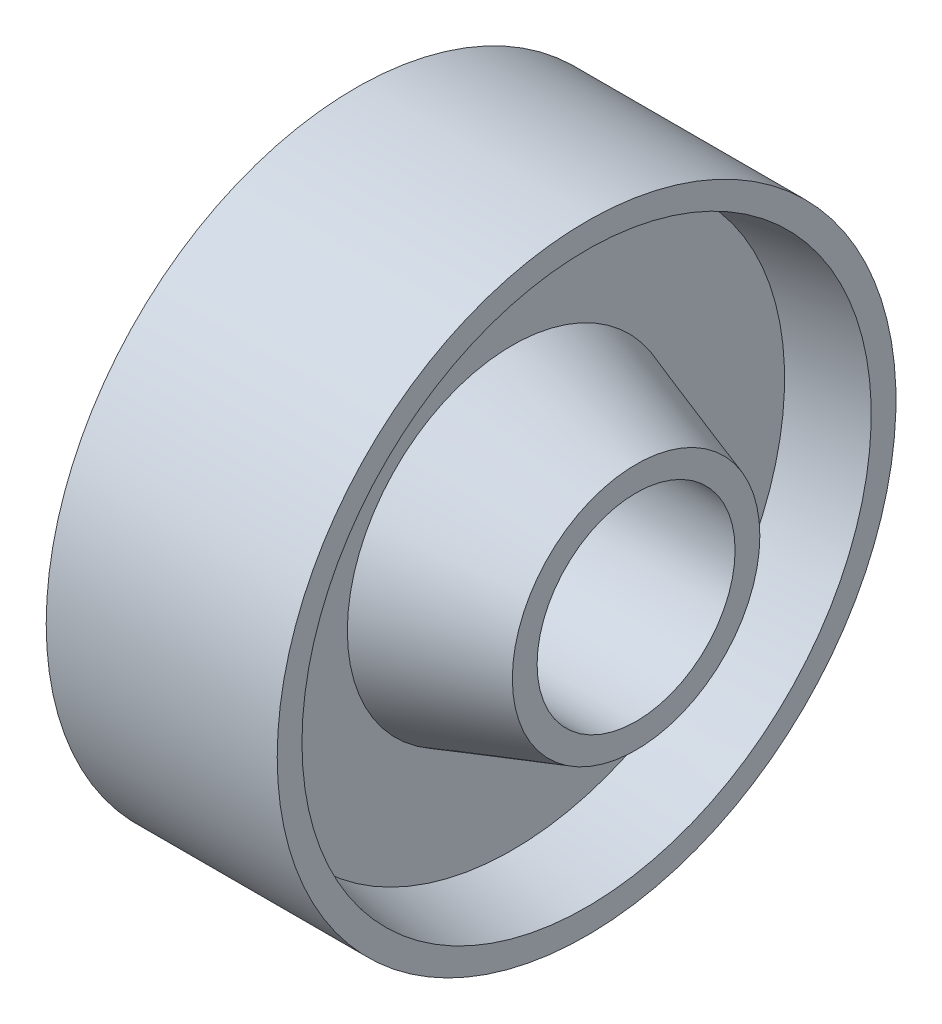
SolidWorks part; units mm, degrees
ref_plane "Front Plane" through (0, 0, 0) normal (0, 0, 1) x (1, 0, 0)
ref_plane "Top Plane" through (0, 0, 0) normal (0, 1, 0) x (1, 0, 0)
ref_plane "Right Plane" through (0, 0, 0) normal (1, 0, 0) x (0, 0, -1)
sketch "Sketch1" plane through (0, 0, 0) normal (0, 0, 1) x (1, 0, 0)
  line L0 (0, 0) -> (0, -12) construction
  line L1 (-20, -12) -> (20, -12)
  line L2 (0, 0) -> (50000, 0) construction
  line L3 (-20, -15) -> (20, -15)
  line L5 (-5, -20) -> (5, -20)
  line L7 (-5, -33) -> (5, -33)
  line L9 (-14, -34.5) -> (14, -34.5)
  line L11 (-14, -37.5) -> (14, -37.5)
  line L12 (-20, -12) -> (-20, -15)
  line L13 (-20, -15) -> (-5, -20)
  line L14 (-5, -20) -> (-5, -33)
  line L15 (-5, -33) -> (-14, -34.5)
  line L16 (-14, -34.5) -> (-14, -37.5)
  line L17 (20, -12) -> (20, -15)
  line L18 (20, -15) -> (5, -20)
  line L19 (5, -20) -> (5, -33)
  line L20 (5, -33) -> (14, -34.5)
  line L21 (14, -34.5) -> (14, -37.5)
  point P6 (0, -12)
  point P10 (0, -15)
  point P14 (0, -20)
  point P18 (0, -33)
  point P22 (0, -34.5)
  point P26 (0, -37.5)
  dimension "D1" = 12
  dimension "D2" = 20
revolve "Revolve1" add sketch "Sketch1" angle 360 about L2
